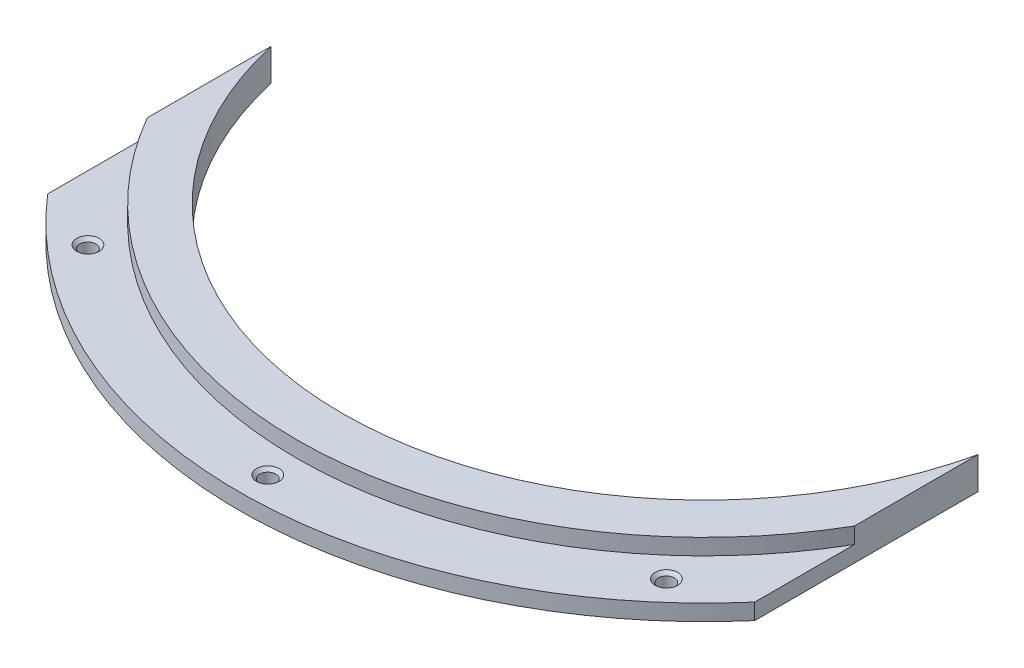
SolidWorks part; units mm, degrees
ref_plane "Front Plane" through (0, 0, 0) normal (0, 0, 1) x (1, 0, 0)
ref_plane "Top Plane" through (0, 0, 0) normal (0, 1, 0) x (1, 0, 0)
ref_plane "Right Plane" through (0, 0, 0) normal (1, 0, 0) x (0, 0, -1)
sketch "Sketch1" plane through (0, 0, 0) normal (0, 1, 0) x (1, 0, 0)
  line L5 (279.4, 247.65) -> (279.4, 198.7875)
  line L13 (0, 198.7875) -> (0, 279.4) construction
  line L14 (0, 279.4) -> (279.4, 279.4) construction
  line L15 (279.4, 198.7875) -> (279.4, 279.4) construction
  line L16 (0, 198.7875) -> (0, 247.65)
  arc A1 (0, 247.65) -> (279.4, 247.65) centre (139.7, 279.4) ccw
  arc A2 (0, 198.7875) -> (279.4, 198.7875) centre (139.7, 279.4) ccw
  point P7 (279.4, 247.65)
  dimension "D3" = 31.75
  dimension "D4" = 279.4
  dimension "D5" = 161.29
  dimension "D1" = 279.4
  dimension "D2" = 139.7
extrude "Boss-Extrude1" add sketch "Sketch1" along normal blind 12.7
sketch "Sketch2" plane through (0, 0, 0) normal (0, -1, 0) x (1, 0, 0)
  line L0 (0, -198.7875) -> (0, -159.4203)
  line L1 (279.4, -198.7875) -> (279.4, -159.4203)
  arc A0 (279.4, -198.7875) -> (0, -198.7875) centre (139.7, -279.4) ccw construction
  arc A1 (279.4, -198.7875) -> (0, -198.7875) centre (139.7, -279.4) ccw
  arc A2 (279.4, -159.4203) -> (0, -159.4203) centre (139.7, -279.4) ccw
  dimension "D1" = 184.15
extrude "Boss-Extrude2" add sketch "Sketch2" against normal blind 6.35
sketch "Sketch3" plane through (0, 6.35, 0) normal (0, 1, 0) x (1, 0, 0)
  line L0 (0, 247.65) -> (0, 198.7875) construction
  line L2 (0, 159.4203) -> (0, 198.7875) construction
  line L3 (279.4, 198.7875) -> (279.4, 159.4203) construction
  circle A0 centre (139.7, 106.68) radius 3.175
  circle A1 centre (25.4, 149.9098) radius 3.175
  circle A2 centre (254, 149.9098) radius 3.175
  circle A3 centre (139.7, 279.4) radius 172.72 construction
  dimension "D1" = 345.44
  dimension "D3" = 6.35
  dimension "D2" = 139.7
  dimension "D4" = 25.4
  dimension "D5" = 25.4
extrude "Cut-Extrude1" cut sketch "Sketch3" against normal blind 12.7
chamfer "Chamfer1" distance 1.27 angle 45 3 edges at (254, 6.35, -146.7348) (139.7, 6.35, -103.505) (25.4, 6.35, -146.7348)
